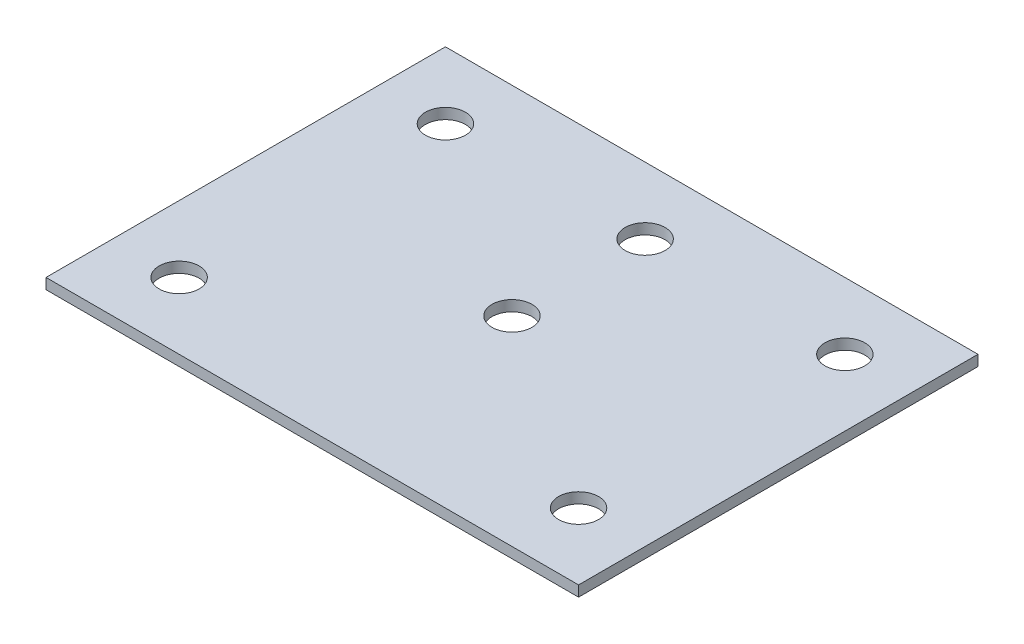
SolidWorks part; units mm, degrees
ref_plane "前视基准面" through (0, 0, 0) normal (0, 0, 1) x (1, 0, 0)
ref_plane "上视基准面" through (0, 0, 0) normal (0, 1, 0) x (1, 0, 0)
ref_plane "右视基准面" through (0, 0, 0) normal (1, 0, 0) x (0, 0, -1)
other "Configuration Table"
sketch "草图1" plane through (0, 0, 0) normal (0, 1, 0) x (1, 0, 0)
  line L0 (-30, 4.2077) -> (-30, -49995.7923) construction
  line L1 (-40, 30) -> (40, 30)
  line L2 (-40, 30) -> (-40, -30)
  line L3 (-40, -30) -> (40, -30)
  line L4 (40, 30) -> (40, -30)
  line L5 (-40, 30) -> (40, -30) construction
  line L6 (-40, -30) -> (40, 30) construction
  line L7 (30, 8.9071) -> (30, -49991.0929) construction
  line L8 (0, 0) -> (0, -50000) construction
  circle A0 centre (-30, 20) radius 3
  circle A1 centre (-30, -20) radius 3
  circle A2 centre (30, -20) radius 3
  circle A3 centre (30, 20) radius 3
  circle A4 centre (0, 20) radius 3
  circle A5 centre (0, 0) radius 3
  point P0 (0, 0)
  dimension "D5" = 6
  dimension "D6" = 6
  dimension "D7" = 6
  dimension "D8" = 6
  dimension "D13" = 6
  dimension "D15" = 6
  dimension "D1" = 80
  dimension "D2" = 60
  dimension "D3" = 10
  dimension "D4" = 10
  dimension "D9" = 10
  dimension "D10" = 10
  dimension "D11" = 10
  dimension "D12" = 10
  dimension "D14" = 10
extrude "凸台-拉伸1" add sketch "草图1" along normal blind 1.6
